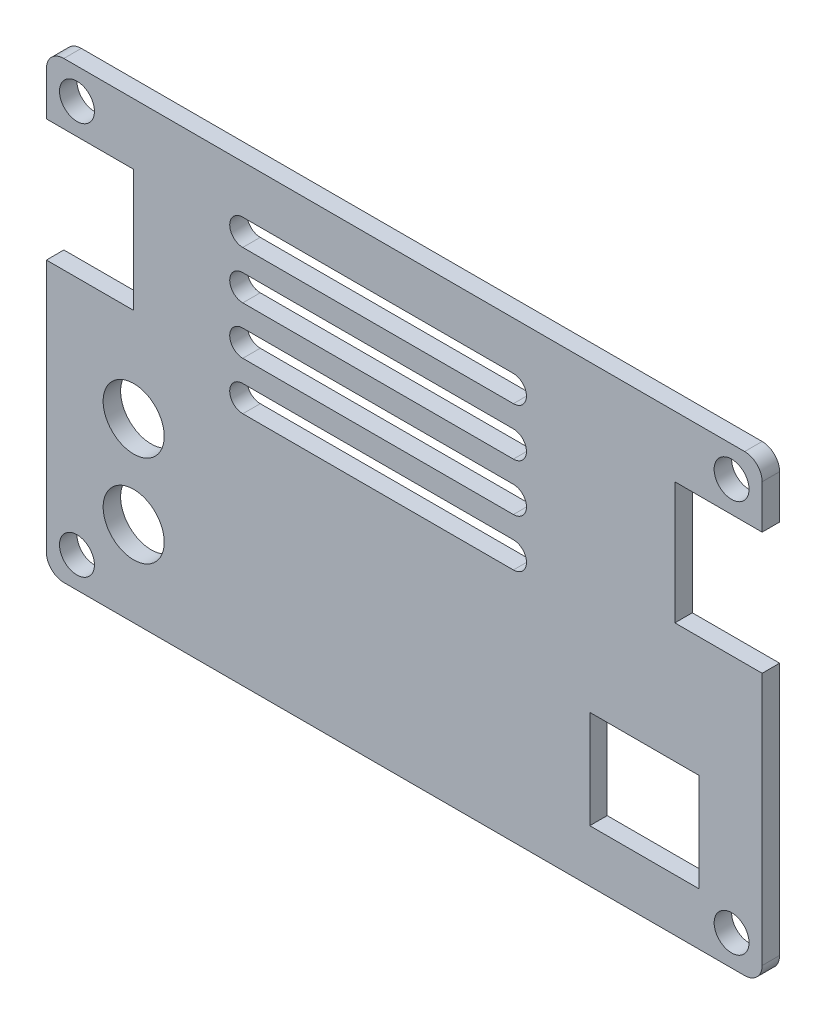
SolidWorks part; units mm, degrees
ref_plane "Front" through (0, 0, 0) normal (0, 0, 1) x (1, 0, 0)
ref_plane "Top" through (0, 0, 0) normal (0, 1, 0) x (1, 0, 0)
ref_plane "Right" through (0, 0, 0) normal (1, 0, 0) x (0, 0, -1)
sketch "Sketch1" plane through (0, 0, 0) normal (0, 0, 1) x (1, 0, 0)
  line L1 (41, -26) -> (-41, -26)
  line L2 (41, -26) -> (41, 26)
  line L3 (41, 26) -> (-41, 26)
  line L4 (-41, -26) -> (-41, 26)
  line L5 (41, -26) -> (-41, 26) construction
  line L6 (41, 26) -> (-41, -26) construction
  point P0 (0, 0)
  dimension "D1" = 82
  dimension "D2" = 52
extrude "Boss-Extrude1" add sketch "Sketch1" along normal blind 2
fillet "Fillet1" radius 2 4 edges at (41, -26, 1) (-41, -26, 1) (-41, 26, 1) (41, 26, 1)
sketch "Sketch2" plane through (0, 0, 2) normal (0, 0, 1) x (1, 0, 0)
  line L0 (-18.5, 19) -> (12.5, 19) construction
  line L1 (-18.5, 20.5) -> (12.5, 20.5)
  line L2 (-18.5, 17.5) -> (12.5, 17.5)
  line L3 (39, 26) -> (-39, 26) construction
  line L4 (-41, 24) -> (-41, -24) construction
  line L5 (-18.5, 13.5) -> (12.5, 13.5) construction
  line L6 (-18.5, 15) -> (12.5, 15)
  line L7 (-18.5, 12) -> (12.5, 12)
  line L8 (-18.5, 8) -> (12.5, 8) construction
  line L9 (-18.5, 9.5) -> (12.5, 9.5)
  line L10 (-18.5, 6.5) -> (12.5, 6.5)
  line L11 (-18.5, 2.5) -> (12.5, 2.5) construction
  line L12 (-18.5, 4) -> (12.5, 4)
  line L13 (-18.5, 1) -> (12.5, 1)
  arc A0 (-18.5, 20.5) -> (-18.5, 17.5) centre (-18.5, 19) ccw
  arc A1 (12.5, 17.5) -> (12.5, 20.5) centre (12.5, 19) ccw
  arc A2 (-18.5, 15) -> (-18.5, 12) centre (-18.5, 13.5) ccw
  arc A3 (12.5, 12) -> (12.5, 15) centre (12.5, 13.5) ccw
  arc A4 (-18.5, 9.5) -> (-18.5, 6.5) centre (-18.5, 8) ccw
  arc A5 (12.5, 6.5) -> (12.5, 9.5) centre (12.5, 8) ccw
  arc A6 (-18.5, 4) -> (-18.5, 1) centre (-18.5, 2.5) ccw
  arc A7 (12.5, 1) -> (12.5, 4) centre (12.5, 2.5) ccw
  point P2 (-3, 19)
  point P14 (-3, 13.5)
  point P20 (-3, 8)
  point P27 (-3, 2.5)
  dimension "D1" = 34
  dimension "D2" = 3
  dimension "D3" = 5.5
  dimension "D4" = 21
  dimension "D5" = 4
extrude "Cut-Extrude1" cut sketch "Sketch2" against normal through all
sketch "Sketch3" plane through (0, 0, 2) normal (0, 0, 1) x (1, 0, 0)
  line L0 (37.5, 22.5) -> (37.5, -22.5) construction
  line L1 (37.5, -22.5) -> (-37.5, -22.5) construction
  line L2 (-37.5, -22.5) -> (-37.5, 22.5) construction
  line L3 (-37.5, 22.5) -> (37.5, 22.5) construction
  circle A0 centre (37.5, 22.5) radius 2
  circle A1 centre (-37.5, 22.5) radius 2
  circle A2 centre (37.5, -22.5) radius 2
  circle A3 centre (-37.5, -22.5) radius 2
  point P8 (0, -22.5)
  point P9 (37.5, 0)
  dimension "D3" = 4
  dimension "D1" = 75
  dimension "D2" = 45
extrude "Cut-Extrude2" cut sketch "Sketch3" against normal through all
sketch "Sketch4" plane through (0, 0, 2) normal (0, 0, 1) x (1, 0, 0)
  line L0 (-41, 24) -> (-41, -24) construction
  line L1 (-41, 19) -> (-31, 19)
  line L2 (-41, 19) -> (-41, 5)
  line L3 (-41, 5) -> (-31, 5)
  line L4 (-31, 19) -> (-31, 5)
  line L5 (41, -24) -> (41, 24) construction
  line L6 (41, 19) -> (31, 19)
  line L7 (41, 19) -> (41, 5)
  line L8 (41, 5) -> (31, 5)
  line L9 (31, 19) -> (31, 5)
  line L10 (39, 26) -> (-39, 26) construction
  line L11 (33.75, -20) -> (21.25, -20)
  line L12 (33.75, -20) -> (33.75, -8.75)
  line L13 (33.75, -8.75) -> (21.25, -8.75)
  line L14 (21.25, -20) -> (21.25, -8.75)
  line L15 (-39, -26) -> (39, -26) construction
  circle A0 centre (-31, -5.75) radius 3.5
  circle A1 centre (-31, -16.25) radius 3.5
  dimension "D8" = 7
  dimension "D1" = 14
  dimension "D2" = 10
  dimension "D3" = 7
  dimension "D4" = 11.25
  dimension "D5" = 12.5
  dimension "D6" = 7.25
  dimension "D7" = 6
  dimension "D9" = 10.5
  dimension "D10" = 6.25
  dimension "D11" = 6.5
extrude "Cut-Extrude3" cut sketch "Sketch4" against normal through all
